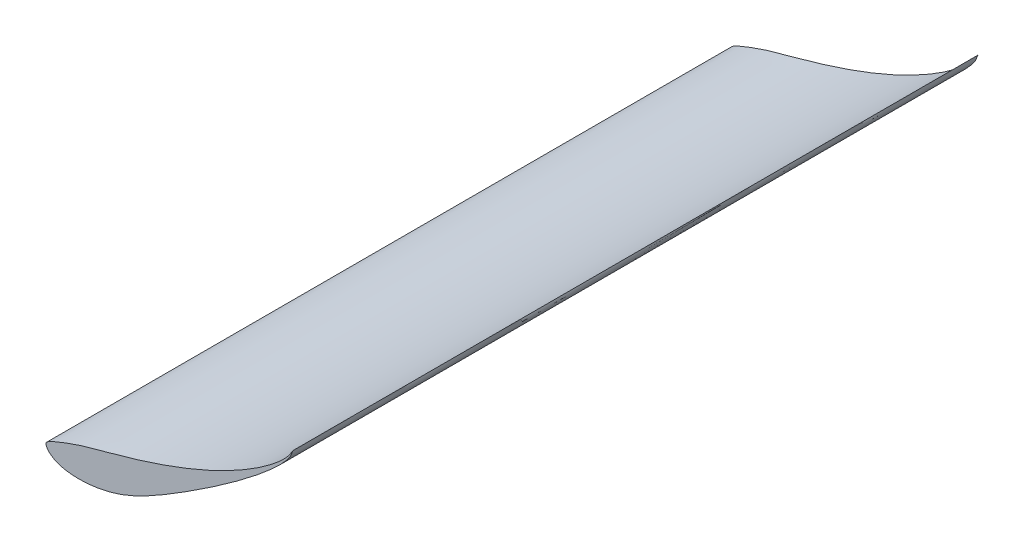
SolidWorks part; units mm, degrees
ref_plane "Front Plane" through (0, 0, 0) normal (0, 0, 1) x (1, 0, 0)
ref_plane "Top Plane" through (0, 0, 0) normal (0, 1, 0) x (1, 0, 0)
ref_plane "Right Plane" through (0, 0, 0) normal (1, 0, 0) x (0, 0, -1)
curve "Curve3"
  spline degree 3 poles (0.9961, 0.0026, 0) (1.0009, -0.0006, 0) (0.9967, 0.0025, 0) (0.9939, 0.0052, 0) (0.9878, 0.0109, 0) (0.9805, 0.017, 0) (0.9705, 0.0231, 0) (0.9581, 0.029, 0) (0.9432, 0.0352, 0) (0.9257, 0.0415, 0) (0.9057, 0.048, 0) (0.8834, 0.0546, 0) (0.8588, 0.0611, 0) (0.8322, 0.0677, 0) (0.8036, 0.0742, 0) (0.7732, 0.0806, 0) (0.7412, 0.0869, 0) (0.7079, 0.0929, 0) (0.6733, 0.0987, 0) (0.6378, 0.1042, 0) (0.6014, 0.1094, 0) (0.5646, 0.1143, 0) (0.5275, 0.1189, 0) (0.4904, 0.1231, 0) (0.4536, 0.1269, 0) (0.4175, 0.1302, 0) (0.3823, 0.1328, 0) (0.3482, 0.1346, 0) (0.3154, 0.1354, 0) (0.284, 0.1353, 0) (0.2541, 0.1338, 0) (0.2258, 0.1307, 0) (0.1988, 0.1263, 0) (0.1732, 0.1206, 0) (0.1489, 0.1139, 0) (0.1262, 0.1063, 0) (0.1051, 0.0981, 0) (0.0858, 0.0892, 0) (0.0682, 0.0798, 0) (0.0525, 0.0701, 0) (0.0388, 0.0602, 0) (0.0271, 0.0502, 0) (0.0176, 0.0401, 0) (0.0103, 0.03, 0) (0.0049, 0.0202, 0) (0.0014, 0.0108, 0) (-0.0002, 0.0022, 0) (0.0001, -0.0051, 0) (0.002, -0.0118, 0) (0.0089, -0.0151, 0) (0.0183, -0.0156, 0) (0.0312, -0.016, 0) (0.0473, -0.0153, 0) (0.0666, -0.0141, 0) (0.0888, -0.012, 0) (0.1137, -0.0092, 0) (0.1411, -0.0057, 0) (0.1711, -0.0007, 0) (0.2038, 0.0055, 0) (0.2393, 0.0123, 0) (0.2775, 0.0195, 0) (0.3182, 0.0267, 0) (0.361, 0.0338, 0) (0.4056, 0.0404, 0) (0.4517, 0.0464, 0) (0.4987, 0.0515, 0) (0.5464, 0.0555, 0) (0.5941, 0.0584, 0) (0.6414, 0.06, 0) (0.6878, 0.0602, 0) (0.7328, 0.059, 0) (0.7758, 0.0564, 0) (0.8164, 0.0525, 0) (0.854, 0.0475, 0) (0.8881, 0.0414, 0) (0.9184, 0.0345, 0) (0.9444, 0.027, 0) (0.9656, 0.0191, 0) (0.9807, 0.0119, 0) (0.9918, 0.0052, 0) (0.9961, 0.0026, 0) (1.0009, -0.0006, 0) (0.9967, 0.0025, 0) knots -0.009748 -0.004147 -0.001 0 0.00098 0.003649 0.007483 0.012095 0.017526 0.024052 0.031783 0.040678 0.05071 0.061833 0.073989 0.087118 0.101145 0.115991 0.13157 0.147788 0.164551 0.181758 0.199312 0.217095 0.23499 0.252857 0.270541 0.287887 0.304773 0.321101 0.336806 0.3518 0.366031 0.379616 0.392653 0.40517 0.417172 0.428604 0.439419 0.449597 0.459102 0.467908 0.475988 0.483309 0.489875 0.495803 0.501149 0.505903 0.510047 0.513579 0.516447 0.51935 0.523823 0.529974 0.537716 0.546968 0.557637 0.56962 0.582804 0.597247 0.613135 0.630444 0.649056 0.668822 0.689595 0.71119 0.733427 0.756094 0.778989 0.80189 0.824567 0.846792 0.868338 0.888978 0.908492 0.926659 0.943286 0.958169 0.971136 0.981956 0.990252 0.995853 0.999 1 1.00098 1.003649 1.007483 periodic
sketch "Sketch4" plane through (0, 0, 0) normal (0, 0, 1) x (1, 0, 0)
  line L0 (0, 0) -> (215.6756, 0) construction
  spline S0 degree 3 poles (161.3618, 78.1813) (161.8787, 79.0828) (161.4473, 78.2475) (161.2128, 77.5868) (160.6637, 76.1779) (159.9637, 74.6226) (158.8341, 72.848) (157.2971, 70.9124) (155.3652, 68.7325) (153.0352, 66.324) (150.3169, 63.7005) (147.2224, 60.8793) (143.7697, 57.8753) (139.9759, 54.709) (135.8619, 51.4001) (131.4522, 47.9686) (126.7741, 44.4345) (121.8518, 40.825) (116.7186, 37.1581) (111.4009, 33.4615) (105.9367, 29.7517) (100.3603, 26.0538) (94.7138, 22.3913) (89.0476, 18.7824) (83.403, 15.2686) (77.823, 11.8851) (72.3337, 8.6819) (66.9568, 5.6976) (61.7065, 2.9807) (56.6231, 0.518) (51.6693, -1.5904) (46.8337, -3.3254) (42.1201, -4.7426) (37.5266, -5.8408) (33.0824, -6.6688) (28.8135, -7.238) (24.7494, -7.5691) (20.9148, -7.6591) (17.334, -7.5322) (14.0308, -7.1981) (11.0315, -6.6702) (8.3538, -5.9824) (6.0164, -5.1035) (4.0335, -4.0441) (2.3819, -2.8783) (1.0837, -1.6396) (0.1358, -0.3743) (-0.3884, 0.8313) (-0.6125, 2.0621) (0.255, 3.1505) (1.7371, 3.9667) (3.7792, 5.0531) (6.447, 6.2149) (9.6665, 7.5288) (13.4178, 8.9478) (17.6603, 10.4616) (22.3792, 12.0507) (27.6222, 13.6122) (33.4008, 15.1821) (39.6853, 16.8885) (46.434, 18.7454) (53.5848, 20.782) (61.0677, 23.0187) (68.8104, 25.4674) (76.7316, 28.1372) (84.7506, 31.0234) (92.7773, 34.1281) (100.726, 37.4307) (108.5071, 40.91) (116.0307, 44.5397) (123.212, 48.2809) (129.97, 52.0886) (136.2234, 55.9167) (141.9061, 59.7028) (146.9503, 63.3846) (151.3074, 66.8974) (154.9143, 70.1415) (157.7205, 73.095) (159.5967, 75.4605) (160.873, 77.424) (161.3618, 78.1813) (161.8787, 79.0828) (161.4473, 78.2475) knots -0.009748 -0.004147 -0.001 0 0.00098 0.003649 0.007483 0.012095 0.017526 0.024052 0.031783 0.040678 0.05071 0.061833 0.073989 0.087118 0.101145 0.115991 0.13157 0.147788 0.164551 0.181758 0.199312 0.217095 0.23499 0.252857 0.270541 0.287887 0.304773 0.321101 0.336806 0.3518 0.366031 0.379616 0.392653 0.40517 0.417172 0.428604 0.439419 0.449597 0.459102 0.467908 0.475988 0.483309 0.489875 0.495803 0.501149 0.505903 0.510047 0.513579 0.516447 0.51935 0.523823 0.529974 0.537716 0.546968 0.557637 0.56962 0.582804 0.597247 0.613135 0.630444 0.649056 0.668822 0.689595 0.71119 0.733427 0.756094 0.778989 0.80189 0.824567 0.846792 0.868338 0.888978 0.908492 0.926659 0.943286 0.958169 0.971136 0.981956 0.990252 0.995853 0.999 1 1.00098 1.003649 1.007483 only from (161.7829, 78.9068) to (161.7829, 78.9068)
extrude "Boss-Extrude1" add sketch "Sketch4" along normal mid plane 450
